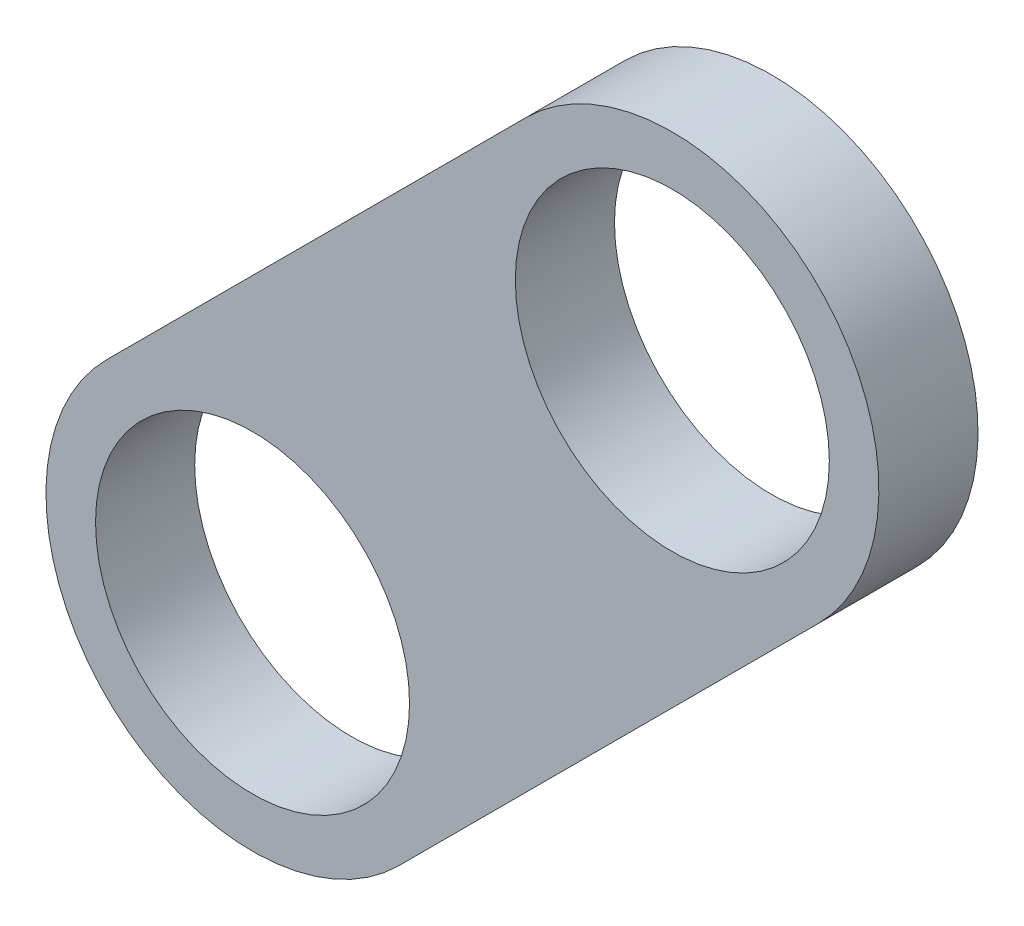
SolidWorks part; units mm, degrees
ref_plane "Front Plane" through (0, 0, 0) normal (0, 0, 1) x (1, 0, 0)
ref_plane "Top Plane" through (0, 0, 0) normal (0, 1, 0) x (1, 0, 0)
ref_plane "Right Plane" through (0, 0, 0) normal (1, 0, 0) x (0, 0, -1)
sketch "Sketch1" plane through (0, 0, 0) normal (0, 0, 1) x (1, 0, 0)
  line L0 (0, 0) -> (25.4, 25.4) construction
  line L1 (-8.8388, 8.8388) -> (16.5612, 34.2388)
  line L2 (8.8388, -8.8388) -> (34.2388, 16.5612)
  arc A0 (-8.8388, 8.8388) -> (8.8388, -8.8388) centre (0, 0) ccw
  arc A1 (34.2388, 16.5612) -> (16.5612, 34.2388) centre (25.4, 25.4) ccw
  circle A2 centre (0, 0) radius 9.5
  circle A3 centre (25.4, 25.4) radius 9.5
  point P0 (0, 0)
  point P1 (25.4, 25.4)
  point P5 (12.7, 12.7)
  dimension "D3" = 12.5
  dimension "D4" = 19
  dimension "D5" = 19
  dimension "D1" = 25.4
  dimension "D2" = 25.4
extrude "Boss-Extrude1" add sketch "Sketch1" along normal blind 6
